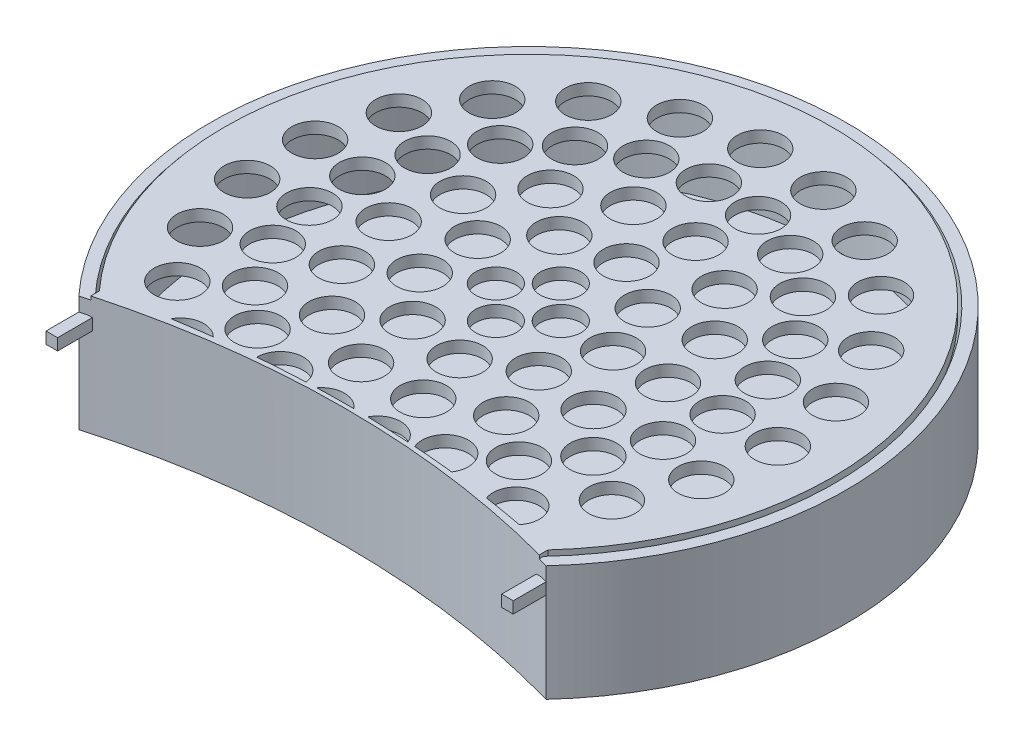
SolidWorks part; units mm, degrees
ref_plane "Front Plane" through (0, 0, 0) normal (0, 0, 1) x (1, 0, 0)
ref_plane "Top Plane" through (0, 0, 0) normal (0, 1, 0) x (1, 0, 0)
ref_plane "Right Plane" through (0, 0, 0) normal (1, 0, 0) x (0, 0, -1)
sketch "Sketch1" plane through (0, 0, 0) normal (0, 1, 0) x (1, 0, 0)
  circle A0 centre (0, 0) radius 69.85
  dimension "D1" = 139.7
extrude "Body" add sketch "Sketch1" along normal blind 25.4
ref_plane "Plane above top surface" through (0, 26.162, 0) normal (0, 1, 0) x (1, 0, 0)
sketch "Sketch3" plane through (0, 26.162, 0) normal (0, 1, 0) x (1, 0, 0)
  circle A0 centre (0, 0) radius 66.675
  dimension "D1" = 133.35
shell "Shell1" thickness 2.54
extrude "plate" add sketch "Sketch3" against normal blind 2.54 separate body
sketch "Sketch5" plane through (0, 26.162, 0) normal (0, 1, 0) x (1, 0, 0)
  line L0 (0, 0) -> (66.675, 0) construction
  circle A1 centre (0, 0) radius 66.675 construction
  circle A2 centre (54.7895, 0) radius 5.08
  circle A3 centre (42.6546, 0) radius 5.08
  dimension "D1" = 10.16
  dimension "D3" = 10.16
  dimension "D2" = 54.7895
  dimension "D4" = 42.6546
extrude "Cut-Extrude2" cut sketch "Sketch5" against normal blind 2.54
pattern_circular "CirPattern1" count 23 over 360 about axis through (0, 0, 0) along (0, 1, 0) of "Cut-Extrude2"
sketch "Sketch6" plane through (0, 26.162, 0) normal (0, 1, 0) x (1, 0, 0)
  line L0 (0, 0) -> (59.8695, 0) construction
  circle A1 centre (54.7895, 0) radius 5.08 construction
  circle A2 centre (30.6672, 0) radius 5.08
  dimension "D2" = 10.16
  dimension "D1" = 59.8695
  dimension "D3" = 30.6672
extrude "Cut-Extrude3" cut sketch "Sketch6" against normal blind 2.54
pattern_circular "CirPattern2" count 14 over 360 about axis through (0, 0, 0) along (0, 1, 0) of "Cut-Extrude3"
sketch "Sketch7" plane through (0, 26.162, 0) normal (0, 1, 0) x (1, 0, 0)
  line L0 (0, 0) -> (66.675, 0) construction
  circle A1 centre (0, 0) radius 66.675 construction
  circle A2 centre (18.6026, 0) radius 5.08
  dimension "D2" = 10.16
  dimension "D1" = 66.675
  dimension "D3" = 18.6026
extrude "Cut-Extrude4" cut sketch "Sketch7" against normal blind 2.54
pattern_circular "CirPattern3" count 9 over 360 about axis through (0, 0, 0) along (0, 1, 0) of "Cut-Extrude4"
sketch "Sketch8" plane through (0, 26.162, 0) normal (0, 1, 0) x (1, 0, 0)
  line L0 (0, 0) -> (18.6734, 0) construction
  circle A0 centre (7.1296, 0) radius 4.445
  dimension "D1" = 8.89
  dimension "D2" = 7.1296
  dimension "D3" = 18.6734
extrude "Cut-Extrude5" cut sketch "Sketch8" against normal blind 2.54
pattern_circular "CirPattern4" count 4 over 360 about axis through (0, 0, 0) along (0, 1, 0) of "Cut-Extrude5"
sketch "Sketch13" plane through (0, 25.4, 0) normal (0, 1, 0) x (1, 0, 0)
  line L4 (49.2375, -86.868) -> (-49.2375, -86.868)
  line L5 (-49.2375, -86.868) -> (-49.2375, -44.958)
  line L6 (49.2375, -86.868) -> (49.2375, -44.958)
  arc A0 (49.2375, -44.958) -> (-49.2375, -44.958) centre (0, -259.8054) ccw
  circle A1 centre (0, 0) radius 66.675 construction
  point P3 (0, -86.868)
  dimension "D3" = 220.4172
  dimension "D1" = 86.868
  dimension "D2" = 41.91
extrude "Boss-Extrude1" add sketch "Sketch13" against normal mid plane 50.8
sketch "Sketch9" plane through (0, 0, 0) normal (0, 1, 0) x (1, 0, 0)
  line L5 (0, 0) -> (0, -86.8926) construction
  line L6 (69.85, -86.8926) -> (-69.85, -86.8926)
  line L7 (0, 0) -> (69.85, 0) construction
  line L8 (-69.85, -86.8926) -> (-69.85, -53.7204)
  line L9 (69.85, -86.8926) -> (69.85, -53.7204)
  circle A1 centre (0, 0) radius 69.85 construction
  arc A2 (69.85, -53.7204) -> (-69.85, -53.7204) centre (0, -228.6) ccw
  point P5 (0, -86.8926)
  dimension "D1" = 33.1722
  dimension "D2" = 86.8926
  dimension "D3" = 228.6
extrude "circle cut" cut sketch "Sketch9" along normal mid plane 127
sketch "Sketch14" plane through (0, 0, 0) normal (1, 0, 0) x (0, 0, -1)
  line L0 (-23.2671, 26.162) -> (-48.6671, 26.162)
  line L1 (-48.6671, 26.162) -> (-48.6671, 52.5938)
  line L2 (-48.6671, 52.5938) -> (-39.4276, 52.5938)
  line L3 (-39.4276, 52.5938) -> (-23.2671, 26.162)
  dimension "D1" = 25.4
  dimension "D2" = 26.4318
  dimension "D3" = 9.2395
  dimension "D4" = 30.9807
  dimension "D5" = 23.2671
  dimension "D6" = 26.162
extrude "Cut-Extrude6" cut sketch "Sketch14" against normal mid plane 127
ref_plane "connection plane" through (0, 0, 46.99) normal (0, 0, 1) x (1, 0, 0)
sketch "Sketch12" plane through (0, 0, 46.99) normal (0, 0, 1) x (1, 0, 0)
  line L0 (0, 0) -> (0, 22.352) construction
  line L1 (0, 22.352) -> (51.2979, 22.352) construction
  line L2 (-51.2979, 22.352) -> (-48.7579, 22.352)
  line L3 (51.2979, 0) -> (51.2979, 25.4) construction
  line L4 (51.2979, 22.352) -> (48.7579, 22.352)
  line L5 (48.7579, 22.352) -> (48.7579, 19.812)
  line L6 (48.7579, 19.812) -> (51.2979, 19.812)
  line L7 (51.2979, 19.812) -> (51.2979, 22.352)
  line L8 (-48.7579, 22.352) -> (-48.7579, 19.812)
  line L9 (-51.2979, 19.812) -> (-51.2979, 22.352)
  line L10 (-48.7579, 19.812) -> (-51.2979, 19.812)
  dimension "D1" = 22.352
  dimension "D2" = 51.2979
  dimension "D3" = 2.54
  dimension "D4" = 2.54
  dimension "D6" = 2.54
extrude "connectors" add sketch "Sketch12" along normal blind 7.62
